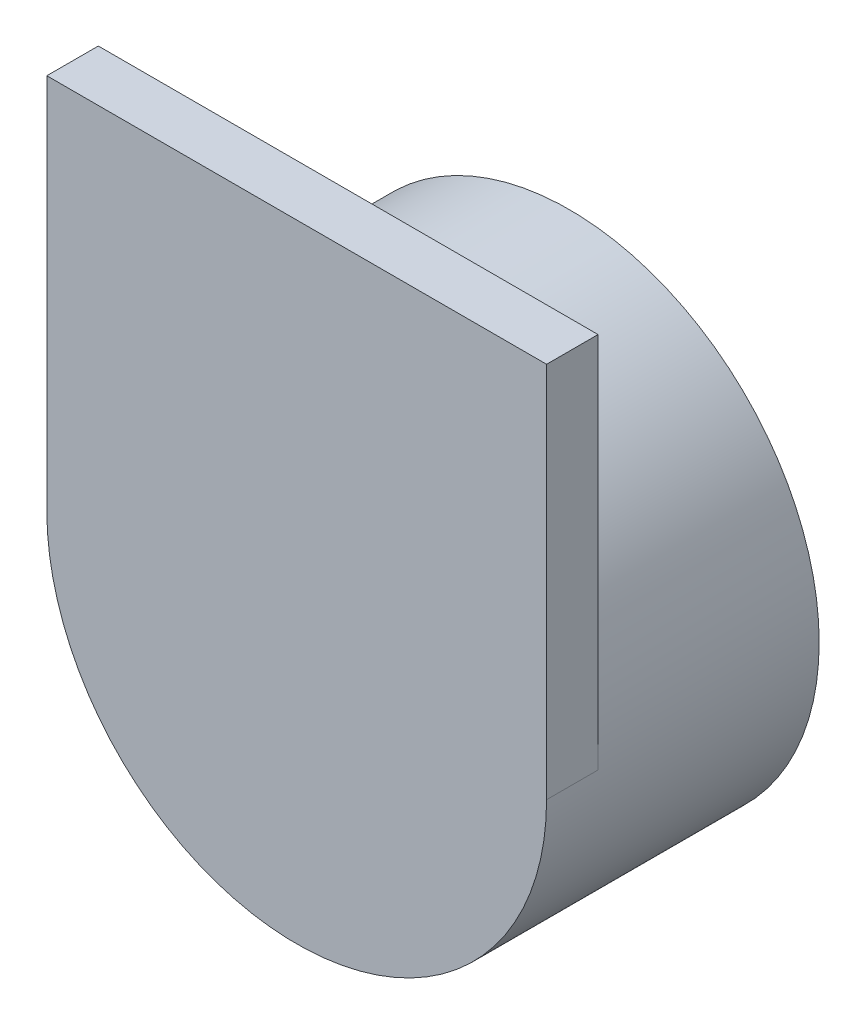
SolidWorks part; units mm, degrees
ref_plane "Front Plane" through (0, 0, 0) normal (0, 0, 1) x (1, 0, 0)
ref_plane "Top Plane" through (0, 0, 0) normal (0, 1, 0) x (1, 0, 0)
ref_plane "Right Plane" through (0, 0, 0) normal (1, 0, 0) x (0, 0, -1)
sketch "Sketch1" plane through (0, 0, 0) normal (0, 0, 1) x (1, 0, 0)
  circle A0 centre (0, 0) radius 8.25
  dimension "D1" = 16.5
extrude "Boss-Extrude1" add sketch "Sketch1" along normal blind 9
sketch "Sketch2" plane through (0, 0, 9) normal (0, 0, 1) x (1, 0, 0)
  line L0 (-8.25, 12.45) -> (8.25, 12.45)
  line L1 (8.25, 12.45) -> (8.25, 0)
  line L2 (-8.25, 12.45) -> (-8.25, 0)
  line L3 (-8.25, 0) -> (8.25, 0)
  circle A0 centre (0, 0) radius 8.25 construction
  dimension "D1" = 12.45
extrude "Boss-Extrude2" add sketch "Sketch2" against normal blind 1.7
